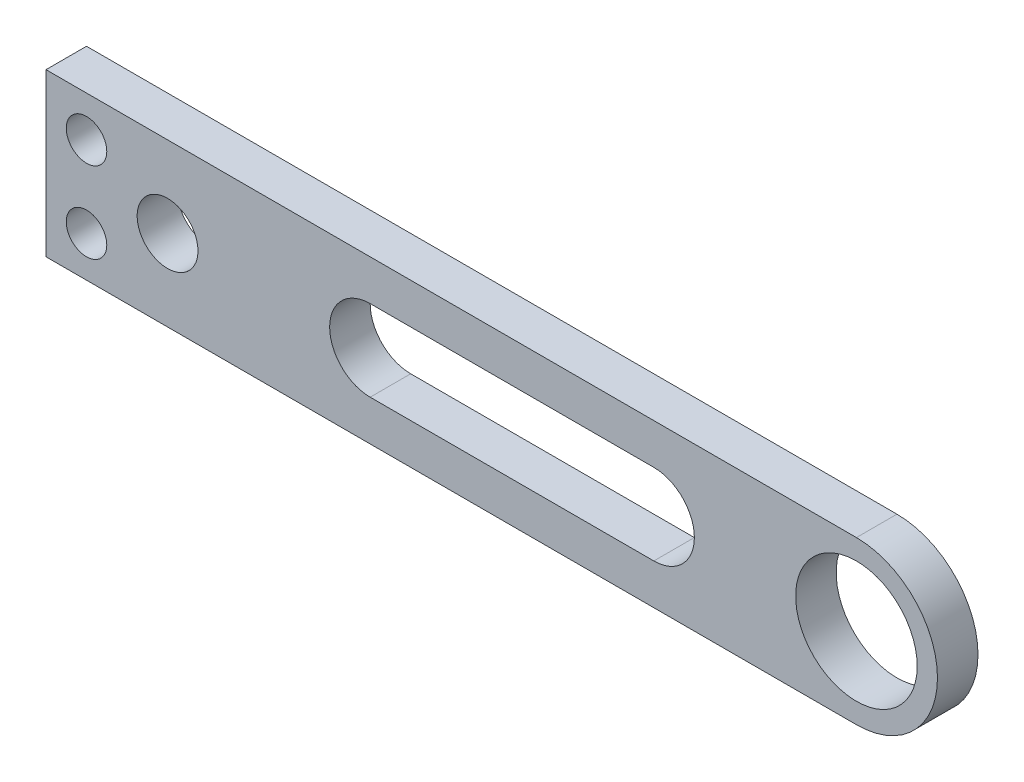
SolidWorks part; units mm, degrees
ref_plane "前视" through (0, 0, 0) normal (0, 0, 1) x (1, 0, 0)
ref_plane "上视" through (0, 0, 0) normal (0, 1, 0) x (1, 0, 0)
ref_plane "右视" through (0, 0, 0) normal (1, 0, 0) x (0, 0, -1)
sketch "草图2" plane through (0, 0, 0) normal (0, 0, 1) x (1, 0, 0)
  line L0 (0, 4) -> (34, 4)
  line L1 (0, -4) -> (34, -4)
  line L2 (10, 2) -> (24, 2)
  line L3 (10, -2) -> (24, -2)
  line L4 (-6, 0) -> (37.0477, 0) construction
  line L5 (0, 4) -> (-6, 4)
  line L6 (-6, 4) -> (-6, -4)
  line L7 (-6, -4) -> (0, -4)
  circle A0 centre (-4, 2) radius 1
  arc A1 (34, -4) -> (34, 4) centre (34, 0) ccw
  circle A2 centre (0, 0) radius 1.5
  circle A3 centre (34, 0) radius 3
  arc A4 (10, 2) -> (10, -2) centre (10, 0) ccw
  arc A5 (24, -2) -> (24, 2) centre (24, 0) ccw
  circle A6 centre (-4, -2) radius 1
  dimension "D1" = 6
  dimension "D2" = 8
  dimension "D3" = 3
  dimension "D4" = 6
  dimension "D8" = 4
  dimension "D9" = 4
  dimension "D12" = 2
  dimension "D15" = 2
  dimension "D5" = 34
  dimension "D6" = 10
  dimension "D7" = 10
  dimension "D10" = 2
  dimension "D11" = 2
  dimension "D13" = 2
  dimension "D14" = 2
extrude "凸台-拉伸1" add sketch "草图2" along normal blind 2
